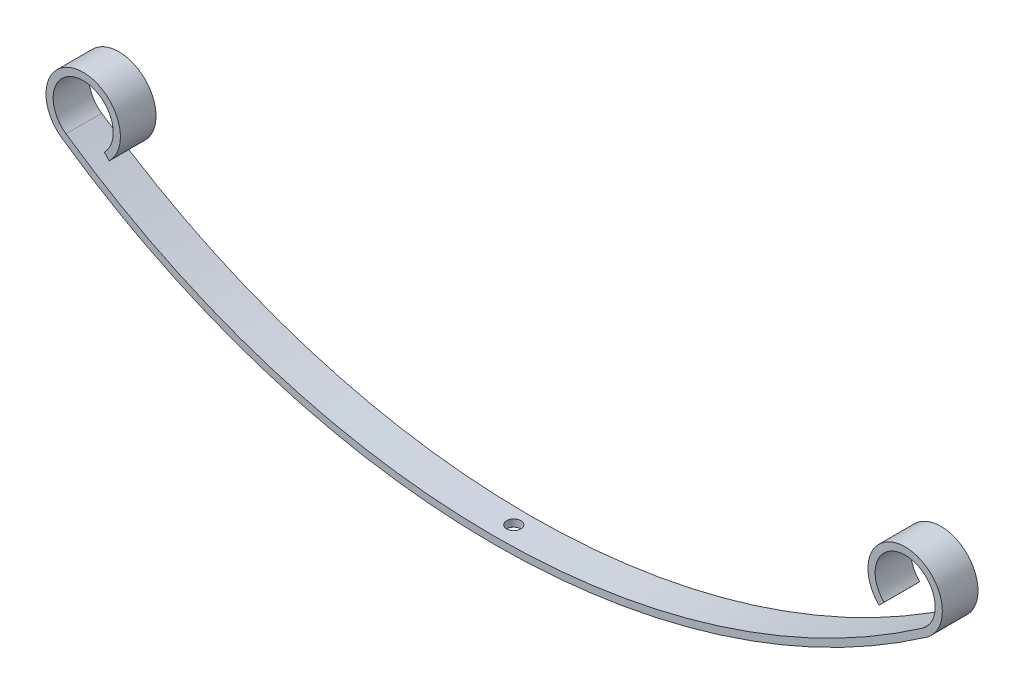
SolidWorks part; units mm, degrees
ref_plane "Front Plane" through (0, 0, 0) normal (0, 0, 1) x (1, 0, 0)
ref_plane "Top Plane" through (0, 0, 0) normal (0, 1, 0) x (1, 0, 0)
ref_plane "Right Plane" through (0, 0, 0) normal (1, 0, 0) x (0, 0, -1)
sketch "Sketch1" plane through (0, 0, 0) normal (0, 0, 1) x (1, 0, 0)
  line L1 (0, 0) -> (0, -3000.7365)
  line L3 (-546.3716, -857.1055) -> (-539.3488, -864.2245)
  line L4 (539.3488, -864.2245) -> (546.3716, -857.1055)
  arc A0 (-605.7143, -869.8909) -> (605.7143, -869.8909) centre (0, 0) ccw
  arc A1 (-600, -861.6844) -> (600, -861.6844) centre (0, 0) ccw
  arc A2 (-539.3488, -864.2245) -> (-605.7143, -869.8909) centre (-575.9405, -827.1316) ccw
  arc A3 (-546.3716, -857.1055) -> (-600, -861.6844) centre (-575.9405, -827.1316) ccw
  arc A4 (546.3716, -857.1055) -> (600, -861.6844) centre (575.9405, -827.1316) cw
  arc A5 (539.3488, -864.2245) -> (605.7143, -869.8909) centre (575.9405, -827.1316) cw
  dimension "D1" = 2120
  dimension "D2" = 2100
extrude "Boss-Extrude1" add sketch "Sketch1" along normal blind 50 contours A0 A5 L4 A4 A1 A3 L3 A2
sketch "Sketch3" plane through (0, 0, 0) normal (0, 1, 0) x (1, 0, 0)
  line L0 (0, 0) -> (0, -53.543) construction
  line L1 (600, 0) -> (-600, 0) construction
  circle A0 centre (0, -22.5) radius 10
  dimension "D1" = 20
  dimension "D2" = 22.5
extrude "Cut-Extrude1" cut sketch "Sketch3" against normal through all
